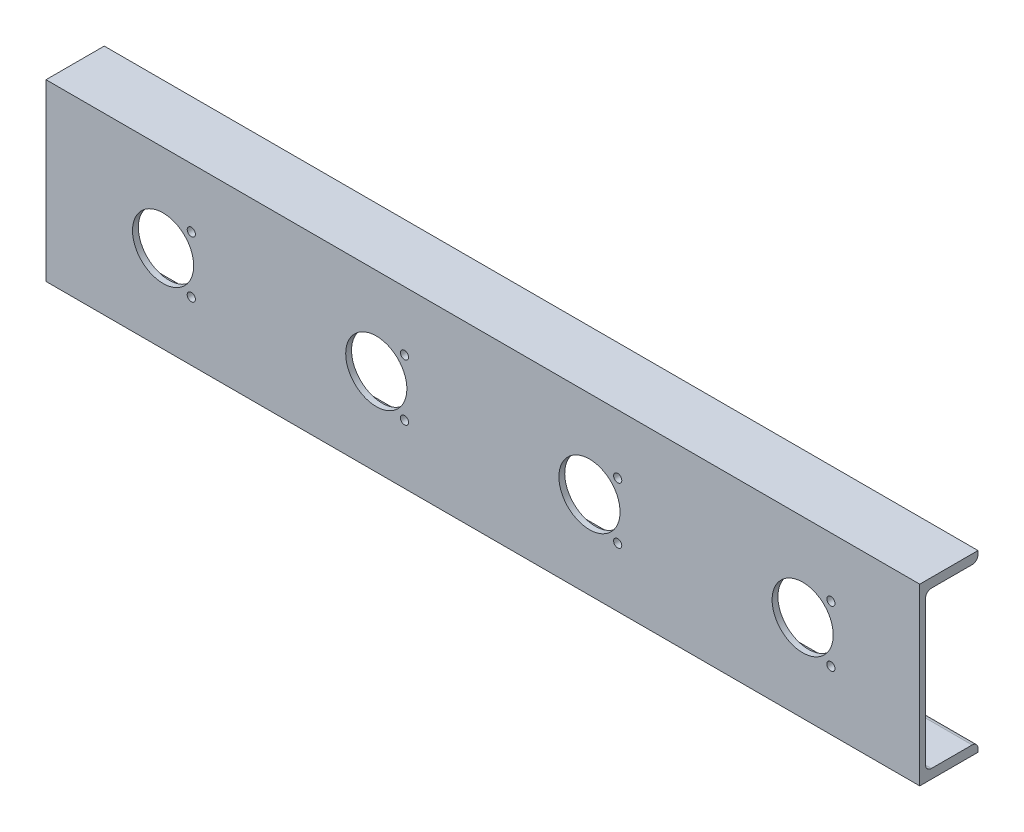
SolidWorks part; units mm, degrees
material "ASTM A36 Steel"
ref_plane "Front Plane" through (0, 0, 0) normal (0, 0, 1) x (1, 0, 0)
ref_plane "Top Plane" through (0, 0, 0) normal (0, 1, 0) x (1, 0, 0)
ref_plane "Right Plane" through (0, 0, 0) normal (1, 0, 0) x (0, 0, -1)
sketch "Sketch1" plane through (0, 0, 0) normal (1, 0, 0) x (0, 0, -1)
  line L0 (-86.6221, 113.8796) -> (-186.6221, 113.8796)
  line L1 (-186.6221, 113.8796) -> (-186.6221, -186.1204)
  line L2 (-186.6221, -186.1204) -> (-86.6221, -186.1204)
  line L3 (-86.6221, -186.1204) -> (-86.6221, -180.1204)
  line L4 (-96.6221, -170.1204) -> (-166.6221, -170.1204)
  line L5 (-176.6221, -160.1204) -> (-176.6221, 87.8796)
  line L6 (-166.6221, 97.8796) -> (-96.6221, 97.8796)
  line L7 (-86.6221, 107.8796) -> (-86.6221, 113.8796)
  arc A0 (-166.6221, -170.1204) -> (-176.6221, -160.1204) centre (-166.6221, -160.1204) cw
  arc A1 (-86.6221, -180.1204) -> (-96.6221, -170.1204) centre (-96.6221, -180.1204) ccw
  arc A2 (-96.6221, 97.8796) -> (-86.6221, 107.8796) centre (-96.6221, 107.8796) ccw
  arc A3 (-176.6221, 87.8796) -> (-166.6221, 97.8796) centre (-166.6221, 87.8796) cw
  point P12 (-86.6221, -170.1204)
  point P15 (-86.6221, 97.8796)
  dimension "D7" = 10
  dimension "D1" = 300
  dimension "D2" = 100
  dimension "D3" = 100
  dimension "D4" = 10
  dimension "D5" = 16
  dimension "D6" = 16
extrude "Boss-Extrude1" add sketch "Sketch1" along normal blind 1500
ref_plane "Plane1" through (650, 0, 0) normal (1, 0, 0) x (0, 0, -1)
sketch "Sketch5" plane through (0, 0, 176.6221) normal (0, 0, -1) x (-1, 0, 0)
  line L0 (-1500, -160.1204) -> (-1500, 87.8796) construction
  line L1 (-1500, 113.8796) -> (0, 113.8796) construction
  circle A0 centre (-1299, -36.1204) radius 52.5
  dimension "D1" = 105
  dimension "D2" = 201
  dimension "D3" = 150
extrude "Cut-Extrude3" cut sketch "Sketch5" against normal blind 30
pattern_linear "LPattern2" count 4 spacing 366 along (-1, 0, 0) of "Cut-Extrude3"
sketch "Sketch6" plane through (0, 0, 186.6221) normal (0, 0, 1) x (1, 0, 0)
  circle A1 centre (1347.4368, 12.3164) radius 7
  circle A3 centre (1347.4368, -84.5572) radius 7
  dimension "D2" = 14
extrude "Cut-Extrude4" cut sketch "Sketch6" against normal through all both and the other way through all
pattern_linear "LPattern3" count 4 spacing 366 along (-1, 0, 0) of "Cut-Extrude4"
